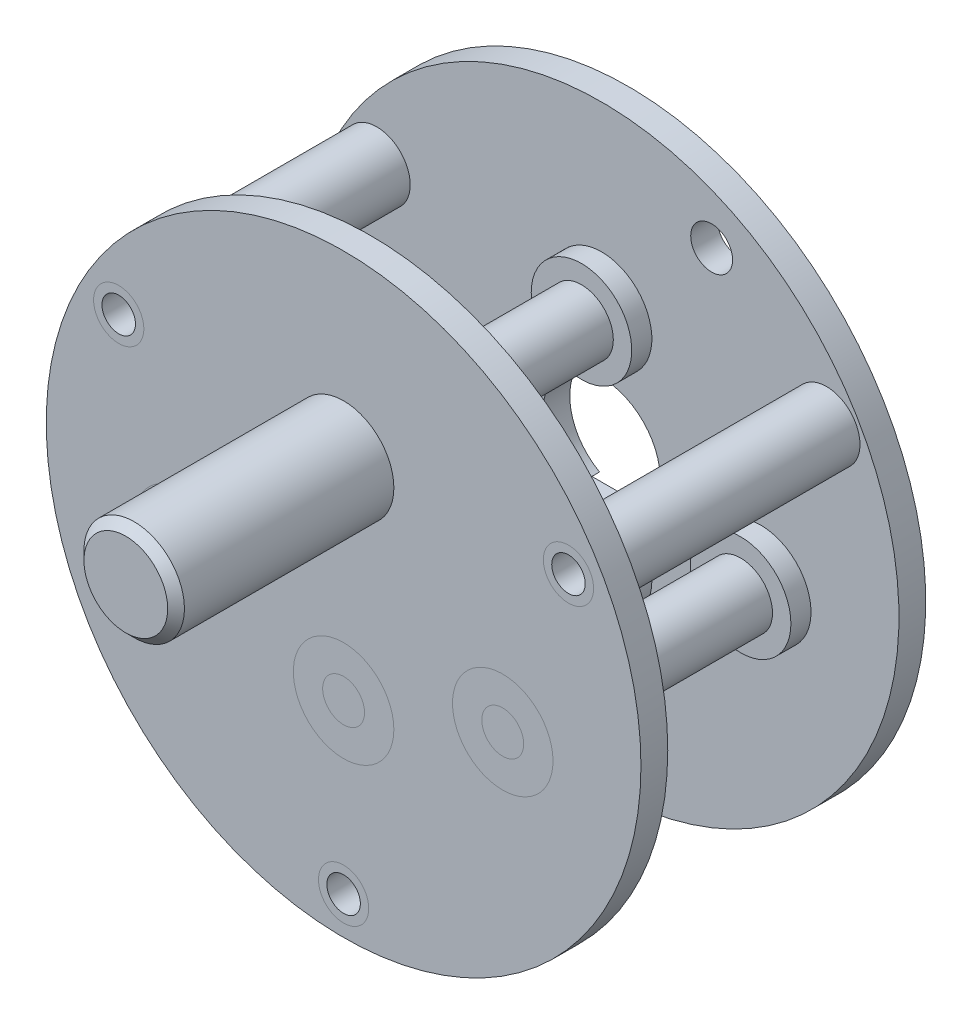
SolidWorks part; units mm, degrees
ref_plane "正面" through (0, 0, 0) normal (0, 0, 1) x (1, 0, 0)
ref_plane "平面" through (0, 0, 0) normal (0, 1, 0) x (1, 0, 0)
ref_plane "右側面" through (0, 0, 0) normal (1, 0, 0) x (0, 0, -1)
sketch "ｽｹｯﾁ1" plane through (0, 0, 0) normal (0, 0, 1) x (1, 0, 0)
  circle A0 centre (0, 0) radius 17.75
  dimension "D1" = 35.5
extrude "ﾎﾞｽ - 押し出し1" add sketch "ｽｹｯﾁ1" along normal blind 1.6
sketch "ｽｹｯﾁ2" plane through (0, 0, 0) normal (0, 0, -1) x (-1, 0, 0)
  circle A0 centre (0, -15.5) radius 2
  circle A2 centre (0, 0) radius 17.75 construction
  circle A3 centre (-13.4234, 7.75) radius 2
  circle A5 centre (13.4234, 7.75) radius 2
  point P14 (0, 0)
  dimension "D1" = 4
  dimension "D2" = 15.5
  dimension "D3" = 3
extrude "ﾎﾞｽ - 押し出し2" add sketch "ｽｹｯﾁ2" along normal blind 13.8
sketch "ｽｹｯﾁ3" plane through (0, 0, -13.8) normal (0, 0, -1) x (-1, 0, 0)
  circle A0 centre (0, 0) radius 17.75
  circle A1 centre (0, 0) radius 17.75 construction
extrude "ﾎﾞｽ - 押し出し3" add sketch "ｽｹｯﾁ3" along normal blind 1.6
sketch "ｽｹｯﾁ5" plane through (0, 0, -15.4) normal (0, 0, -1) x (-1, 0, 0)
  circle A0 centre (0, -15.5) radius 2 construction
  circle A1 centre (13.4234, 7.75) radius 2 construction
  circle A2 centre (-13.4234, 7.75) radius 2 construction
  circle A3 centre (0, -15.5) radius 2 construction
  circle A4 centre (13.4234, 7.75) radius 2 construction
  circle A5 centre (-13.4234, 7.75) radius 2 construction
  circle A6 centre (0, 0) radius 3.5
  circle A7 centre (-13.4234, 7.75) radius 1
  circle A8 centre (13.4234, 7.75) radius 1
  circle A9 centre (0, -15.5) radius 1
  dimension "D1" = 7
  dimension "D2" = 1
extrude "ｶｯﾄ - 押し出し2" cut sketch "ｽｹｯﾁ5" against normal up to next
sketch "ｽｹｯﾁ6" plane through (0, 0, 1.6) normal (0, 0, 1) x (1, 0, 0)
  circle A0 centre (0, 7) radius 6
  circle A1 centre (0, 0) radius 17.75 construction
  dimension "D1" = 7
  dimension "D2" = 12
extrude "ﾎﾞｽ - 押し出し4" add sketch "ｽｹｯﾁ6" along normal blind 10
sketch "ｽｹｯﾁ7" plane through (0, 0, 11.6) normal (0, 0, 1) x (1, 0, 0)
  circle A0 centre (0, 7) radius 3
  dimension "D1" = 6
extrude "ﾎﾞｽ - 押し出し5" add sketch "ｽｹｯﾁ7" along normal blind 15
chamfer "面取り1" distance 0.5 angle 45 1 edges at (3, 7, 26.6)
sketch "ｽｹｯﾁ8" plane through (0, 0, 26.6) normal (0, 0, 1) x (1, 0, 0)
  line L0 (1.6583, 9.5) -> (-1.6583, 9.5)
  circle A0 centre (0, 7) radius 3 construction
  arc A1 (1.6583, 9.5) -> (-1.6583, 9.5) centre (0, 7) ccw
  dimension "D1" = 2.5
extrude "ｶｯﾄ - 押し出し3" cut sketch "ｽｹｯﾁ8" against normal blind 12
sketch "ｽｹｯﾁ9" plane through (0, 0, 1.6) normal (0, 0, 1) x (1, 0, 0)
  circle A4 centre (0, -15.5) radius 1.5
  circle A5 centre (-13.4234, 7.75) radius 1.5
  circle A6 centre (13.4234, 7.75) radius 1.5
  point P9 (0, 0)
  dimension "D1" = 3
  dimension "D2" = 3
split line "分割ﾗｲﾝ1"
sketch "ｽｹｯﾁ10" plane through (0, 0, 1.6) normal (0, 0, 1) x (1, 0, 0)
  line L0 (-9.5, -2.3775) -> (0, -5.5) construction
  line L1 (0, -5.5) -> (9.5, -2.3775) construction
  circle A0 centre (0, -5.5) radius 3
  circle A1 centre (9.5, -2.3775) radius 3
  circle A2 centre (-9.5, -2.3775) radius 3
  circle A3 centre (0, 0) radius 17.75 construction
  dimension "D2" = 5.5
  dimension "D3" = 19
  dimension "D4" = 6
  dimension "D1" = 10
extrude "ﾎﾞｽ - 押し出し6" add sketch "ｽｹｯﾁ10" against normal blind 2.8
ref_plane "平面1" through (0, 0, -6.9) normal (0, 0, 1) x (1, 0, 0)
mirror "ﾐﾗｰ1" about plane through (0, 0, -6.9) normal (0, 0, 1) of "ﾎﾞｽ - 押し出し6"
sketch "ｽｹｯﾁ11" plane through (0, 0, 1.6) normal (0, 0, 1) x (1, 0, 0)
  circle A0 centre (0, -5.5) radius 3 construction
  circle A1 centre (-9.5, -2.3775) radius 3 construction
  circle A2 centre (9.5, -2.3775) radius 3 construction
  circle A3 centre (0, -5.5) radius 3
  circle A4 centre (-9.5, -2.3775) radius 3
  circle A5 centre (9.5, -2.3775) radius 3
split line "分割ﾗｲﾝ2"
sketch "ｽｹｯﾁ12" plane through (0, 0, 1.6) normal (0, 0, 1) x (1, 0, 0)
  circle A0 centre (-9.5, -2.3775) radius 1.25
  circle A1 centre (0, -5.5) radius 1.25
  circle A2 centre (9.5, -2.3775) radius 1.25
  circle A3 centre (-9.5, -2.3775) radius 3 construction
  circle A9 centre (0, -5.5) radius 3 construction
  circle A10 centre (9.5, -2.3775) radius 3 construction
  dimension "D1" = 2.5
split line "分割ﾗｲﾝ3"
sketch "ｽｹｯﾁ13" plane through (0, 0, -1.2) normal (0, 0, -1) x (-1, 0, 0)
  circle A1 centre (-9.5, -2.3775) radius 1.9
  circle A2 centre (0, -5.5) radius 1.9
  circle A3 centre (9.5, -2.3775) radius 1.9
  dimension "D1" = 3.8
extrude "ﾎﾞｽ - 押し出し7" add sketch "ｽｹｯﾁ13" along normal up to next
sketch "ｽｹｯﾁ14" plane through (0, 0, -15.4) normal (0, 0, -1) x (-1, 0, 0)
  circle A0 centre (0, 7) radius 6 construction
  circle A1 centre (0, 7) radius 1.25
  circle A2 centre (0, -5.5) radius 1.25 construction
  circle A6 centre (0, 7) radius 3
  circle A9 centre (0, -5.5) radius 3 construction
split line "分割ﾗｲﾝ4"
sketch "ｽｹｯﾁ15" plane through (0, 0, -15.4) normal (0, 0, -1) x (-1, 0, 0)
  line L0 (2.2361, -3.5) -> (-2.2361, -3.5)
  arc A0 (-1.7249, -3.0455) -> (1.7249, -3.0455) centre (0, -5.5) ccw construction
  arc A2 (1.7249, -3.0455) -> (-1.7249, -3.0455) centre (0, 0) ccw construction
  arc A3 (2.2361, -3.5) -> (1.7249, -3.0455) centre (0, -5.5) ccw
  arc A5 (-1.7249, -3.0455) -> (1.7249, -3.0455) centre (0, -5.5) ccw
  arc A6 (1.7249, -3.0455) -> (-1.7249, -3.0455) centre (0, -5.5) ccw
  arc A7 (-1.7249, -3.0455) -> (-2.2361, -3.5) centre (0, -5.5) ccw
  arc A8 (1.7249, -3.0455) -> (-1.7249, -3.0455) centre (0, -5.5) ccw
  dimension "D1" = 0
extrude "ｶｯﾄ - 押し出し4" cut sketch "ｽｹｯﾁ15" against normal up to next
sketch "ｽｹｯﾁ17" plane through (0, 0, -15.4) normal (0, 0, -1) x (-1, 0, 0)
  line L0 (6.5696, -13.4848) -> (-6.5696, 13.4848) construction
  line L1 (9.5, -2.3775) -> (-6.5696, 13.4848) construction
  circle A0 centre (-6.5696, 13.4848) radius 1.25
  circle A1 centre (6.5696, -13.4848) radius 1.25
  circle A2 centre (0, 7) radius 1.25 construction
  circle A3 centre (9.5, -2.3775) radius 1.25 construction
  point P6 (0, 0)
  point P7 (0, 7)
  dimension "D2" = 2.5
  dimension "D1" = 30
extrude "ｶｯﾄ - 押し出し5" cut sketch "ｽｹｯﾁ17" against normal up to next
chamfer "面取り2" distance 0.5 angle 45 1 edges at (6, 7, 11.6)
sketch "ｽｹｯﾁ19" plane through (0, 0, 0) normal (0, 0, -1) x (-1, 0, 0)
  circle A0 centre (0, 7) radius 3 construction
  circle A1 centre (0, 7) radius 3
extrude "ﾎﾞｽ - 押し出し8" add sketch "ｽｹｯﾁ19" along normal up to surface (1.2 mm away) up to face at (1.9, -5.5, -1.2)
sketch "ｽｹｯﾁ20" plane through (0, 0, -1.2) normal (0, 0, -1) x (-1, 0, 0)
  circle A0 centre (0, 7) radius 1.9
  circle A1 centre (0, -5.5) radius 1.9 construction
extrude "ﾎﾞｽ - 押し出し9" add sketch "ｽｹｯﾁ20" along normal up to next
sketch "ｽｹｯﾁ21" plane through (0, 0, -13.8) normal (0, 0, 1) x (1, 0, 0)
  circle A0 centre (0, 7) radius 3 construction
  circle A1 centre (0, 7) radius 3
extrude "ﾎﾞｽ - 押し出し10" add sketch "ｽｹｯﾁ21" along normal up to surface (1.2 mm away) up to face at (7.6, -2.3775, -12.6)
sketch "ｽｹｯﾁ23" plane through (0, 0, 11.6) normal (0, 0, 1) x (1, 0, 0)
  circle A0 centre (0, 7) radius 6
  circle A1 centre (0, 7) radius 6 construction
  circle A2 centre (0, 7) radius 3
  circle A3 centre (0, 7) radius 3 construction
extrude "ｶｯﾄ - 押し出し7" cut sketch "ｽｹｯﾁ23" against normal blind 10
sketch "ｽｹｯﾁ24" plane through (0, 0, 26.6) normal (0, 0, 1) x (1, 0, 0)
  circle A0 centre (0, 7) radius 3
  circle A1 centre (0, 7) radius 3 construction
extrude "ｶｯﾄ - 押し出し8" cut sketch "ｽｹｯﾁ24" against normal blind 12
chamfer "面取り3" distance 0.5 1 edges at (3, 7, 14.6)
sketch "ｽｹｯﾁ25" plane through (0, 0, -15.4) normal (0, 0, -1) x (-1, 0, 0)
  line L0 (-8, 0) -> (8, 0) construction
  line L1 (0, 8) -> (0, -8) construction
  line L2 (-6.2172, 5.0346) -> (6.2172, -5.0346) construction
  line L3 (0, 0) -> (-6.2932, -7.7715) construction
  circle A0 centre (-6.2172, 5.0346) radius 3 construction
  circle A1 centre (6.2172, -5.0346) radius 3 construction
  circle A2 centre (-6.2932, -7.7715) radius 3 construction
  point P12 (-6.4852, -7.612)
  point P13 (-6.4224, 4.7699)
  dimension "D2" = 6
  dimension "D1" = 16
  dimension "D3" = 10
  dimension "D4" = 39
